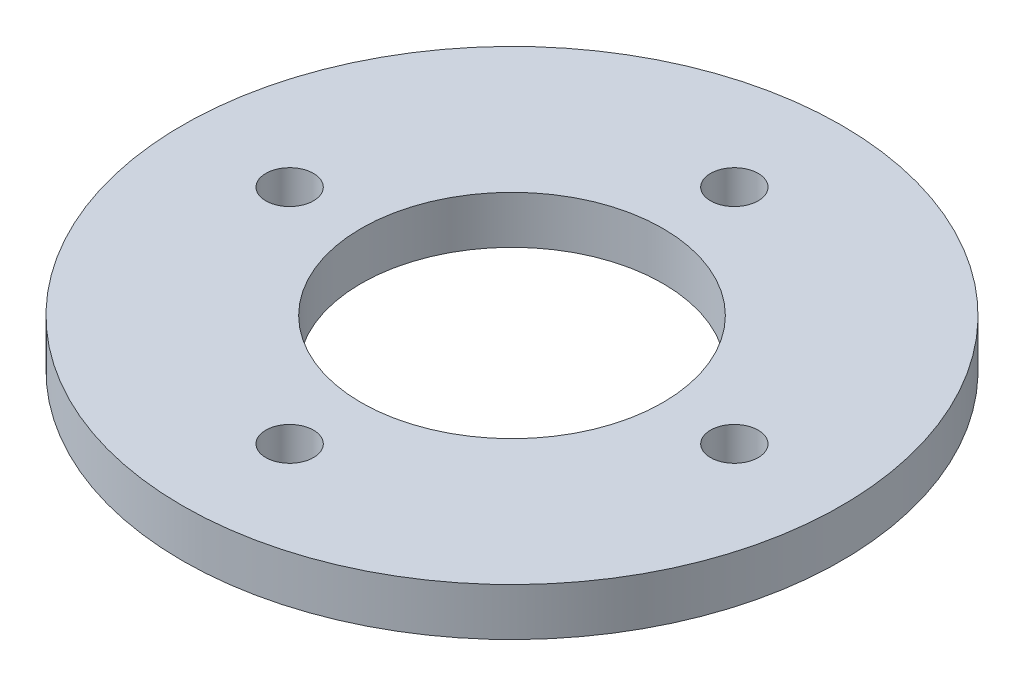
SolidWorks part; units mm, degrees
material "6061 合金"
ref_plane "前视基准面" through (0, 0, 0) normal (0, 0, 1) x (1, 0, 0)
ref_plane "上视基准面" through (0, 0, 0) normal (0, 1, 0) x (1, 0, 0)
ref_plane "右视基准面" through (0, 0, 0) normal (1, 0, 0) x (0, 0, -1)
other "Configuration Table"
sketch "草图1" plane through (0, 0, 0) normal (0, 1, 0) x (1, 0, 0)
  circle A0 centre (0, 0) radius 20.75
  circle A1 centre (0, 0) radius 9.5
  circle A2 centre (14, 0) radius 1.5
  circle A3 centre (0, -14) radius 1.5
  circle A4 centre (-14, 0) radius 1.5
  circle A5 centre (0, 14) radius 1.5
  dimension "D1" = 41.5
  dimension "D2" = 19
  dimension "D3" = 3
  dimension "D4" = 14
extrude "凸台-拉伸2" add sketch "草图1" along normal blind 3 contours A0 A5 A4 A3 A2 A1
